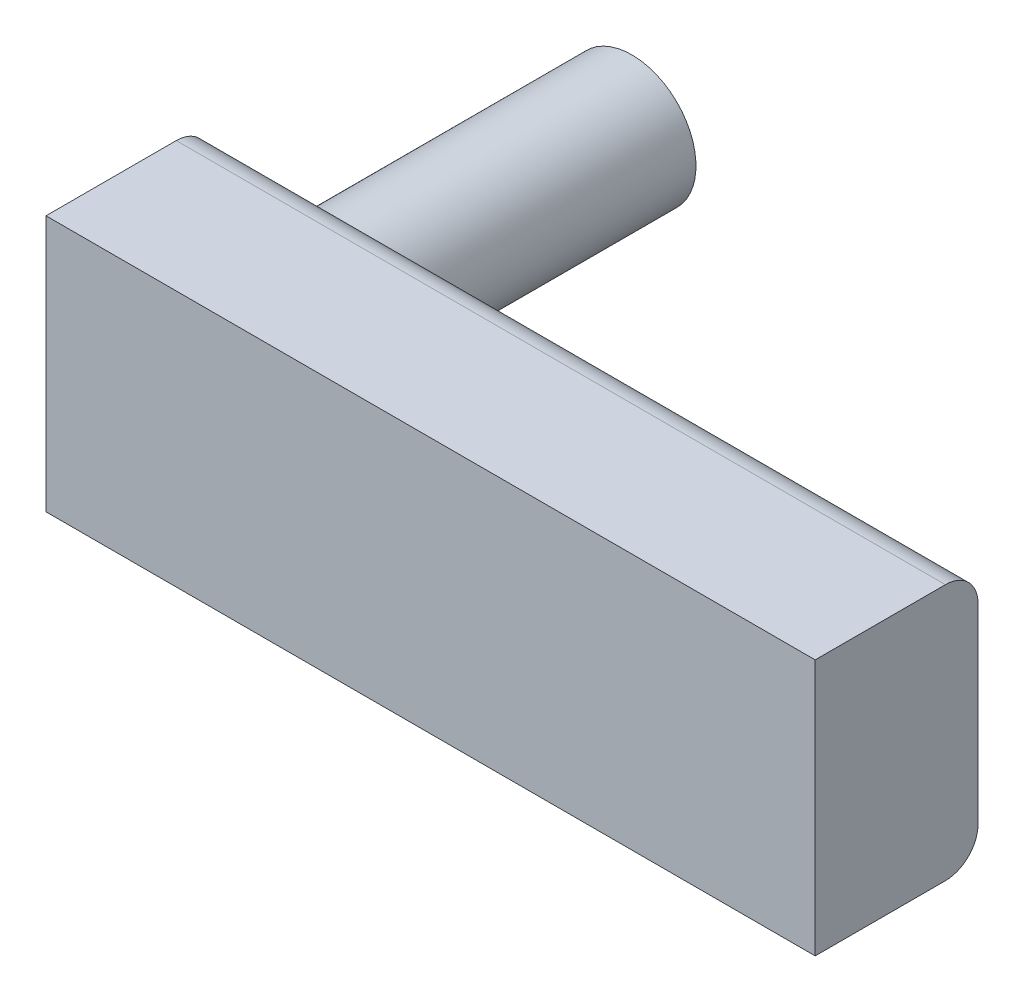
SolidWorks part; units mm, degrees
ref_plane "Front Plane" through (0, 0, 0) normal (0, 0, 1) x (1, 0, 0)
ref_plane "Top Plane" through (0, 0, 0) normal (0, 1, 0) x (1, 0, 0)
ref_plane "Right Plane" through (0, 0, 0) normal (1, 0, 0) x (0, 0, -1)
sketch "Sketch1" plane through (0, 0, 0) normal (0, 0, 1) x (1, 0, 0)
  line L0 (-82.4987, -15.4905) -> (-22.4987, -15.4905)
  line L1 (-22.4987, -15.4905) -> (-22.4987, -35.4905)
  line L2 (-22.4987, -35.4905) -> (-82.4987, -35.4905)
  line L3 (-82.4987, -35.4905) -> (-82.4987, -15.4905)
extrude "Boss-Extrude2" add sketch "Sketch1" along normal blind 12.7
fillet "Fillet1" radius 2.54 1 edges at (-52.4987, -35.4905, 0)
fillet "Fillet2" radius 2.54 1 edges at (-52.4987, -15.4905, 0)
sketch "Sketch2" plane through (0, 0, 0) normal (0, 0, -1) x (-1, 0, 0)
  circle A0 centre (74.899, -24.8666) radius 5
extrude "Boss-Extrude3" add sketch "Sketch2" along normal blind 25.4
